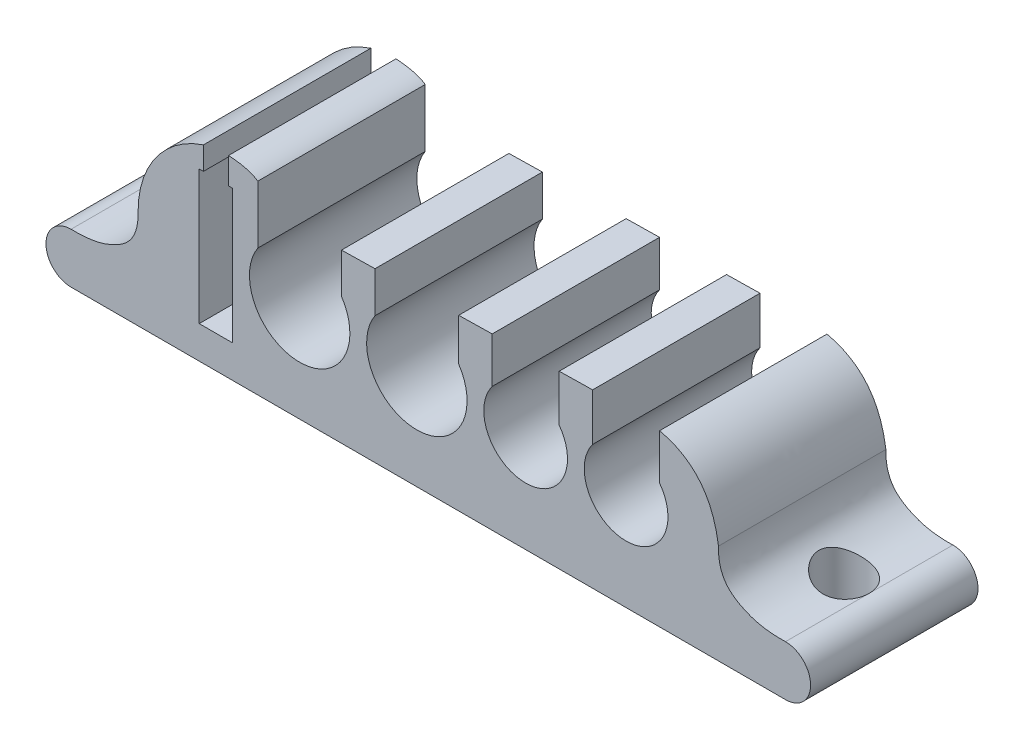
SolidWorks part; units mm, degrees
ref_plane "Front Plane" through (0, 0, 0) normal (0, 0, 1) x (1, 0, 0)
ref_plane "Top Plane" through (0, 0, 0) normal (0, 1, 0) x (1, 0, 0)
ref_plane "Right Plane" through (0, 0, 0) normal (1, 0, 0) x (0, 0, -1)
sketch "Esboço1" plane through (0, 0, 0) normal (0, 0, 1) x (1, 0, 0)
  line L0 (-12.0663, 0) -> (7.4337, 0) construction
  line L6 (-12.0663, 0) -> (-16.0663, 0) construction
  line L7 (-16.0663, 4) -> (-16.0663, -4)
  line L8 (-16.0663, -4) -> (-18.0663, -4)
  line L9 (-18.0663, -4) -> (-18.0663, 4)
  line L10 (-18.0663, 4) -> (-16.0663, 4)
  line L11 (-16.0663, 0) -> (7.4337, 0) construction
  line L13 (-16.132, -5.9427) -> (7.368, -5.9427)
  line L14 (-16.132, -5.9427) -> (-25.7197, -5.9427)
  line L15 (-25.7197, -2.9427) -> (-25.7197, -5.9427) construction
  line L16 (7.368, -5.9427) -> (16.9557, -5.9427)
  line L17 (-4.382, 5.5849) -> (-4.382, -5.9427) construction
  line L18 (7.368, 4.3582) -> (-12.643, 4)
  circle A0 centre (-12.0663, 0) radius 3
  circle A1 centre (-5.0663, 0) radius 3
  circle A2 centre (1.4337, 0) radius 2.5
  circle A3 centre (7.4337, 0) radius 2.5
  arc A4 (-16.9254, 5.5849) -> (-21.7168, 0) centre (-16.0663, 0) ccw
  arc A6 (-25.7197, -2.9427) -> (-25.7197, -5.9427) centre (-25.7197, -4.4427) ccw
  arc A7 (16.9557, -2.9427) -> (16.9557, -5.9427) centre (16.9557, -4.4427) cw
  spline S0 degree 3 poles (-21.7168, 0) (-21.6765, -1.4821) (-23.0305, -2.6197) (-24.5651, -2.9687) (-25.7197, -2.9427) knots 0 0 0 0 0.504814 1 1 1 1
  spline S1 degree 3 poles (12.9529, 0) (12.9125, -1.4821) (14.2665, -2.6197) (15.8011, -2.9687) (16.9557, -2.9427) knots 0 0 0 0 0.504814 1 1 1 1
  spline S2 degree 2 poles (12.9529, 0) (12.3092, 4.6001) (7.368, 4.3582) knots 0 0 0 1 1 1
  spline S3 degree 3 poles (-12.643, 4) (-13.9015, 4.0653) (-14.0437, 5.2712) (-15.8836, 5.5967) (-16.9254, 5.5849) knots 0 0 0 0 0.564228 1 1 1 1
  point P12 (-4.382, 0)
  point P15 (-16.0663, 0)
  point P30 (-13.7209, 4.9695)
  point P37 (-11.4235, 4)
  point P38 (-12.643, 4)
  point P39 (-14.6024, 5.1458)
  point P40 (-16.9254, 5.5849)
  point P41 (0, 0)
  dimension "D1" = 6
  dimension "D2" = 6
  dimension "D3" = 5
  dimension "D4" = 5
  dimension "D11" = 3
  dimension "D5" = 8
  dimension "D6" = 2
  dimension "D7" = 7
  dimension "D8" = 6.5
  dimension "D9" = 6
  dimension "D10" = 4
extrude "Ressalto-extrusão1" add sketch "Esboço1" along normal blind 10
sketch "Esboço4" plane through (0, 0, 0) normal (0, 0, -1) x (-1, 0, 0)
  line L0 (-7.4337, 2.5) -> (-7.4337, 4.3613) construction
  line L1 (-1.4337, 2.5) -> (-1.4337, 4.252) construction
  line L2 (-7.368, 4.3582) -> (12.643, 4) construction
  line L3 (5.0663, 3) -> (5.0663, 4.1356) construction
  line L4 (12.0663, 3) -> (12.0663, 4.0103) construction
  line L5 (17.0663, 4) -> (17.0663, 5.5614) construction
  line L7 (18.0663, 4) -> (16.0663, 4) construction
  line L9 (-9.4337, 5.3613) -> (-5.4337, 5.3613)
  line L10 (-9.4337, 5.3613) -> (-9.4337, 1.5)
  line L11 (-9.4337, 1.5) -> (-5.4337, 1.5)
  line L12 (-5.4337, 5.3613) -> (-5.4337, 1.5)
  line L13 (-9.4337, 5.3613) -> (-5.4337, 1.5) construction
  line L14 (-9.4337, 1.5) -> (-5.4337, 5.3613) construction
  line L15 (-3.4337, 5.252) -> (0.5663, 5.252)
  line L16 (-3.4337, 5.252) -> (-3.4337, 1.5)
  line L17 (-3.4337, 1.5) -> (0.5663, 1.5)
  line L18 (0.5663, 5.252) -> (0.5663, 1.5)
  line L19 (-3.4337, 5.252) -> (0.5663, 1.5) construction
  line L20 (-3.4337, 1.5) -> (0.5663, 5.252) construction
  line L21 (2.5663, 5.4773) -> (7.5663, 5.4773)
  line L22 (2.5663, 5.4773) -> (2.5663, 1.6583)
  line L23 (2.5663, 1.6583) -> (7.5663, 1.6583)
  line L24 (7.5663, 5.4773) -> (7.5663, 1.6583)
  line L25 (2.5663, 5.4773) -> (7.5663, 1.6583) construction
  line L26 (2.5663, 1.6583) -> (7.5663, 5.4773) construction
  line L27 (9.5663, 5.352) -> (14.5663, 5.352)
  line L28 (9.5663, 5.352) -> (9.5663, 1.6583)
  line L29 (9.5663, 1.6583) -> (14.5663, 1.6583)
  line L30 (14.5663, 5.352) -> (14.5663, 1.6583)
  line L31 (9.5663, 5.352) -> (14.5663, 1.6583) construction
  line L32 (9.5663, 1.6583) -> (14.5663, 5.352) construction
  line L33 (17.8163, 3.7411) -> (16.3163, 3.7411)
  line L34 (17.8163, 3.7411) -> (17.8163, 5.8202)
  line L35 (17.8163, 5.8202) -> (16.3163, 5.8202)
  line L36 (16.3163, 3.7411) -> (16.3163, 5.8202)
  line L37 (17.8163, 3.7411) -> (16.3163, 5.8202) construction
  line L38 (17.8163, 5.8202) -> (16.3163, 3.7411) construction
  circle A0 centre (-7.4337, 0) radius 2.5 construction
  circle A1 centre (-1.4337, 0) radius 2.5 construction
  circle A2 centre (5.0663, 0) radius 3 construction
  circle A3 centre (12.0663, 0) radius 3 construction
  arc A4 (21.7168, 0) -> (16.9254, 5.5849) centre (16.0663, 0) ccw construction
  parabola Q0 (-12.9529, 0) -> (-7.368, 4.3582) focus (-10.1415, 1.7895) apex (-11.4228, 3.2331) construction
  point P34 (-7.4337, 3.4306)
  point P39 (-1.4337, 3.376)
  point P44 (5.0663, 3.5678)
  point P49 (12.0663, 3.5052)
  point P54 (17.0663, 4.7807)
  dimension "D1" = 4
  dimension "D2" = 4
  dimension "D3" = 5
  dimension "D4" = 5
  dimension "D5" = 1.5
extrude "Corte-extrusão1" cut sketch "Esboço4" against normal blind 10
sketch "Esboço5" plane through (0, 0, 0) normal (0, 1, 0) x (1, 0, 0)
  line L0 (-25.7197, -5) -> (16.9557, -5) construction
  line L1 (-25.7197, -10) -> (-25.7197, 0) construction
  line L2 (16.9557, -10) -> (16.9557, 0) construction
  circle A0 centre (-24.2197, -5) radius 1.5
  circle A1 centre (15.4557, -5) radius 1.5
  dimension "D1" = 3
  dimension "D2" = 3
extrude "Corte-extrusão2" cut sketch "Esboço5" against normal blind 10
